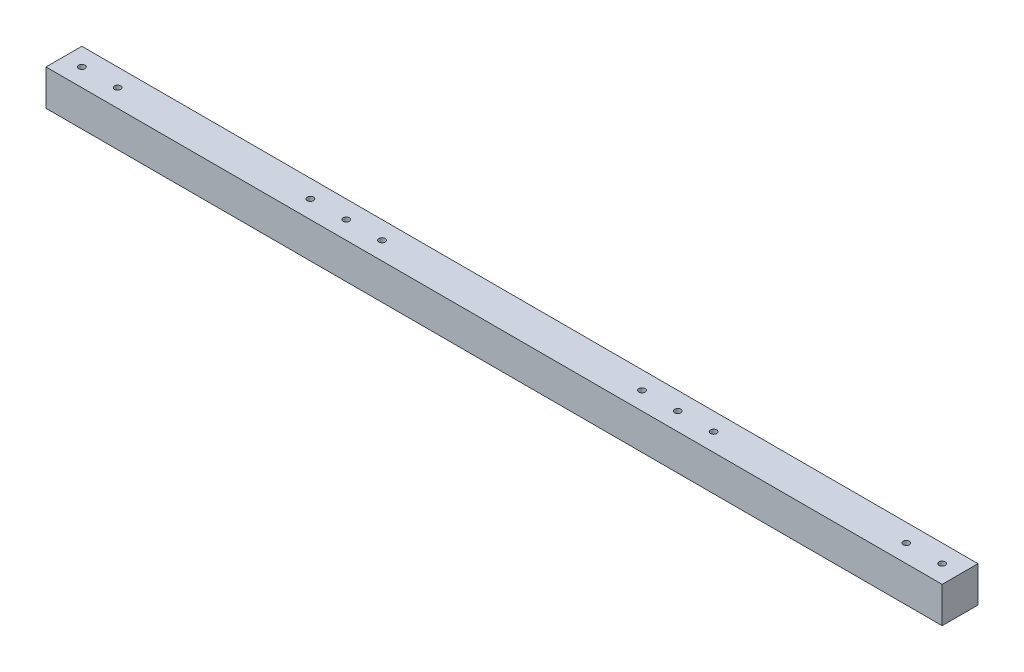
SolidWorks part; units mm, degrees
ref_plane "前视基准面" through (0, 0, 0) normal (0, 0, 1) x (1, 0, 0)
ref_plane "上视基准面" through (0, 0, 0) normal (0, 1, 0) x (1, 0, 0)
ref_plane "右视基准面" through (0, 0, 0) normal (1, 0, 0) x (0, 0, -1)
sketch "草图1" plane through (0, 0, 0) normal (0, 1, 0) x (1, 0, 0)
  line L0 (240, 0) -> (220, 0) construction
  line L1 (-250, 10) -> (250, 10)
  line L2 (-250, 10) -> (-250, -10)
  line L3 (-250, -10) -> (250, -10)
  line L4 (250, 10) -> (250, -10)
  line L5 (-250, 10) -> (250, -10) construction
  line L6 (-250, -10) -> (250, 10) construction
  line L7 (0, 0) -> (0, 40.6872) construction
  circle A0 centre (240, 0) radius 1.75
  circle A1 centre (220, 0) radius 1.75
  circle A2 centre (-240, 0) radius 1.75
  circle A3 centre (-220, 0) radius 1.75
  point P0 (0, 0)
  dimension "D3" = 10
  dimension "D5" = 3.5
  dimension "D1" = 500
  dimension "D2" = 20
  dimension "D4" = 10
  dimension "D7" = 20
  dimension "D6" = 2
extrude "凸台-拉伸1" add sketch "草图1" along normal blind 20
sketch "草图2" plane through (0, 0, 0) normal (0, -1, 0) x (1, 0, 0)
  line L0 (-92.5, 0) -> (-72.5, 0) construction
  line L1 (-100, -24.7798) -> (-85, -24.7798) construction
  line L2 (-100, -24.7798) -> (-100, -71.6458) construction
  line L3 (-100, -71.6458) -> (-85, -71.6458) construction
  line L4 (-85, -24.7798) -> (-85, -71.6458) construction
  line L5 (-92.5, 0) -> (-112.5, 0) construction
  line L6 (-250, 10) -> (250, 10) construction
  line L7 (0, 0) -> (0, -38.2231) construction
  line L8 (100, -71.6458) -> (85, -71.6458) construction
  line L9 (85, -24.7798) -> (85, -71.6458) construction
  line L10 (100, -24.7798) -> (85, -24.7798) construction
  line L11 (100, -24.7798) -> (100, -71.6458) construction
  circle A0 centre (-92.5, 0) radius 1.75
  circle A1 centre (-72.5, 0) radius 1.75
  circle A2 centre (-112.5, 0) radius 1.75
  circle A3 centre (112.5, 0) radius 1.75
  circle A4 centre (92.5, 0) radius 1.75
  circle A5 centre (72.5, 0) radius 1.75
  dimension "D1" = 15
  dimension "D7" = 3.5
  dimension "D2" = 7.5
  dimension "D4" = 20
  dimension "D6" = 20
  dimension "D8" = 10
  dimension "D9" = 170
  dimension "D3" = 2
  dimension "D5" = 2
extrude "切除-拉伸1" cut sketch "草图2" against normal up to next
